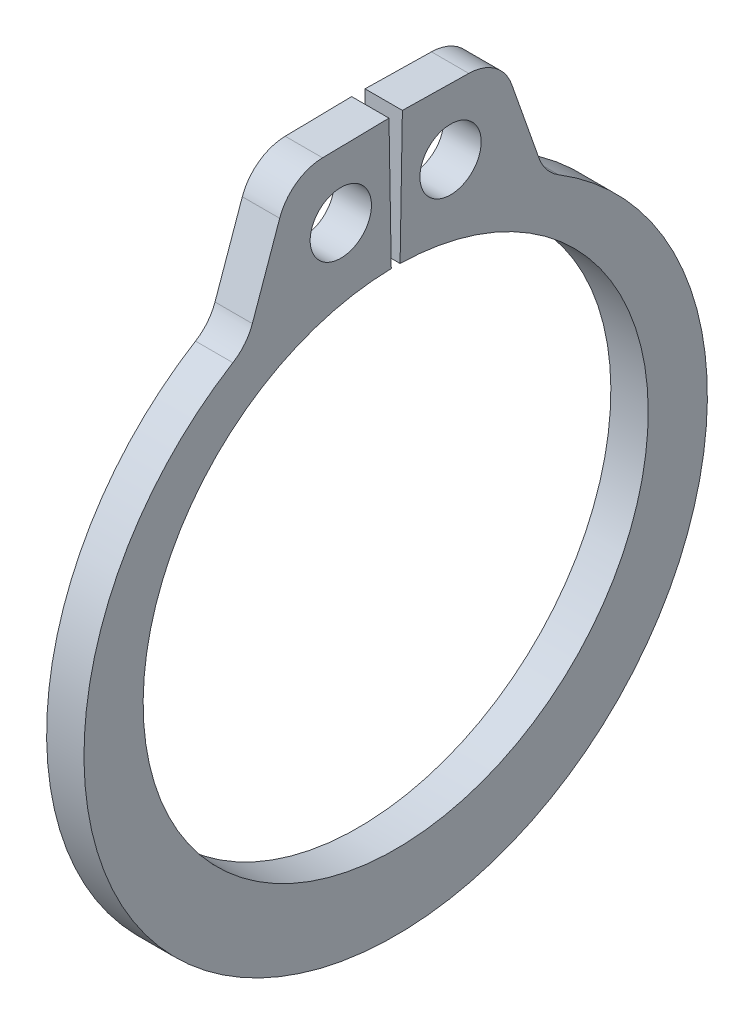
SolidWorks part; units mm, degrees
material "Cast Carbon Steel"
ref_plane "Front" through (0, 0, 0) normal (0, 0, 1) x (1, 0, 0)
ref_plane "Top" through (0, 0, 0) normal (0, 1, 0) x (1, 0, 0)
ref_plane "Right" through (0, 0, 0) normal (1, 0, 0) x (0, 0, -1)
sketch "Sketch1" plane through (0, 0, 0) normal (1, 0, 0) x (0, 0, -1)
  line L0 (0, 0) -> (0, 4.2926) construction
  line L1 (-0.0749, 4.2919) -> (-0.1139, 6.5268)
  line L2 (0.1139, 6.5268) -> (1.7901, 6.4975)
  line L3 (1.7901, 6.4975) -> (2.5323, 4.3892)
  line L4 (0.0749, 4.2919) -> (0.1139, 6.5268)
  line L5 (-0.1139, 6.5268) -> (-1.7901, 6.4975)
  line L6 (-1.7901, 6.4975) -> (-2.5323, 4.3892)
  line L7 (-2.5323, 4.3892) -> (-2.1452, 3.7182) construction
  line L8 (2.5323, 4.3892) -> (2.1452, 3.7182) construction
  line L9 (0, -4.2926) -> (0, -5.5626) construction
  line L10 (-1.7901, 6.4975) -> (-0.0749, 4.2919) construction
  line L11 (0, 4.2926) -> (0, 6.5278) construction
  line L12 (-4.2926, 0) -> (4.2926, 0) construction
  circle A0 centre (0, 0) radius 4.2926 construction
  arc A1 (-0.0749, 4.2919) -> (0.0749, 4.2919) centre (0, 0) ccw
  circle A3 centre (0, 0) radius 7.62 construction
  circle A4 centre (-0.9325, 5.3947) radius 0.5207
  circle A5 centre (0.9325, 5.3947) radius 0.5207
  arc A6 (-2.5323, 4.3892) -> (2.5323, 4.3892) centre (0, -0.2645) ccw
  point P0 (0, -5.5626)
  dimension "A" = 8.5852
  dimension "D2" = 1.6764
  dimension "L" = 15.24
  dimension "Hole" = 1.0414
  dimension "Smin" = 0.7747
  dimension "Smax" = 1.27
  dimension "H" = 2.2352
  dimension "Angle" = 1
extrude "Extrude1" add sketch "Sketch1" along normal mid plane 0.635
fillet "Fillet1" radius 0.7874 4 edges at (0, 4.3892, 2.5323) (0, 4.3892, -2.5323) (0, 6.4975, 1.7901) (0, 6.4975, -1.7901)
sketch "Sketch2" plane through (0, 0, 0) normal (0, 0, 1) x (1, 0, 0)
  line L0 (-3.5433, 0) -> (9.1567, 0)
  line L1 (9.1567, 0) -> (9.1567, -4.7625)
  line L2 (-0.3683, -4.7625) -> (-3.2512, -4.7625)
  line L3 (9.1567, -4.7625) -> (0.3683, -4.7625)
  line L4 (0.3683, -4.7625) -> (0.3683, -4.4704)
  line L5 (0.3683, -4.4704) -> (-0.3683, -4.4704)
  line L6 (-0.3683, -4.4704) -> (-0.3683, -4.7625)
  line L7 (-0.3683, -4.7625) -> (-3.5433, -4.7625) construction
  line L8 (-3.5433, -4.7625) -> (-3.5433, 0) construction
  line L9 (9.1567, 0) -> (76.391, 0) construction
  line L10 (-3.2512, -4.7625) -> (-3.5433, -4.4704)
  line L11 (-3.5433, -4.4704) -> (-3.5433, 0)
  point P10 (0, -4.4704)
  dimension "D1" = 45
  dimension "Dg" = 8.9408
  dimension "Ds" = 9.525
  dimension "W" = 0.7366
  dimension "D2" = 12.7
  dimension "D3" = 3.175
revolve "Revolve1" [suppressed] add sketch "Sketch2" angle 360 about L9
delete or keep bodies "Body-Delete1" [suppressed] type delete bodies bodies 122
equation "\"D2@Sketch2\" = \"D1@Extrude1\"*20"
equation "\"D3@Sketch2\" = \"D2@Sketch2\"/4"
equation "\"D2@Sketch1\" = \"H@Sketch1\"*.75"
